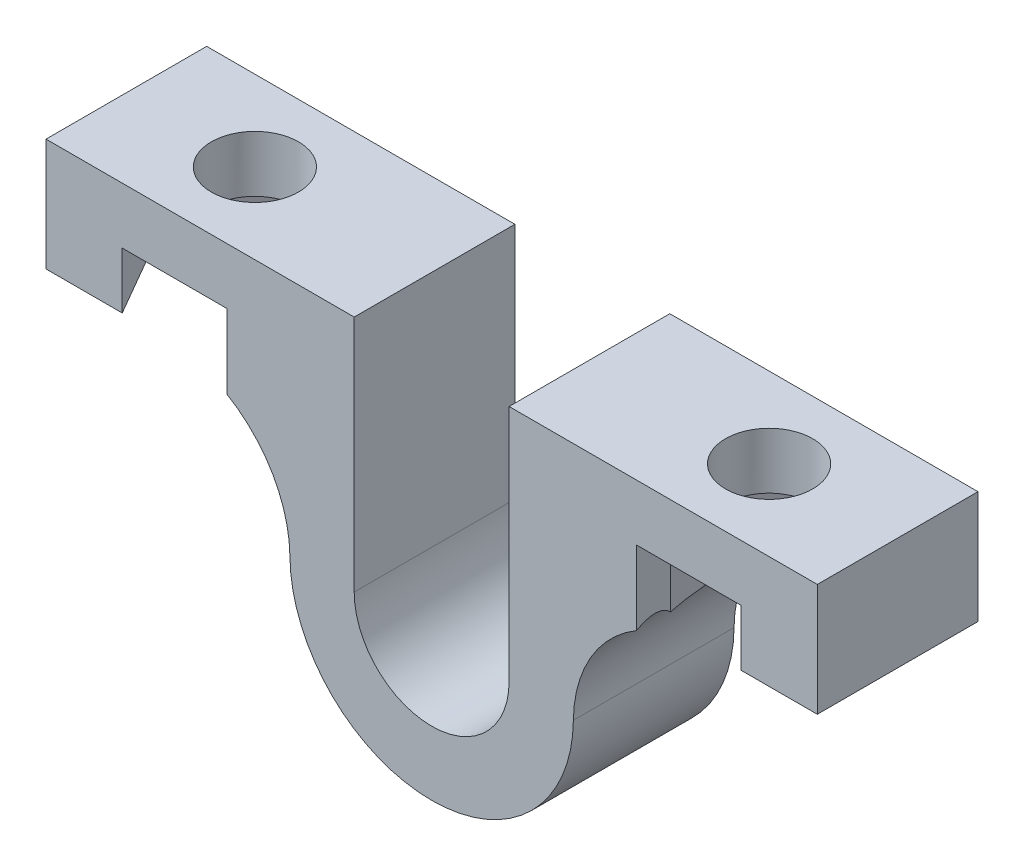
SolidWorks part; units mm, degrees
ref_plane "Front Plane" through (0, 0, 0) normal (0, 0, 1) x (1, 0, 0)
ref_plane "Top Plane" through (0, 0, 0) normal (0, 1, 0) x (1, 0, 0)
ref_plane "Right Plane" through (0, 0, 0) normal (1, 0, 0) x (0, 0, -1)
sketch "Sketch1" plane through (0, 0, 0) normal (0, 0, 1) x (1, 0, 0)
  line L2 (-19.05, 11.7634) -> (-19.05, 6.2071)
  line L6 (-3.8259, 0) -> (-3.8259, 11.7634)
  line L13 (-19.05, 6.2071) -> (-13.3501, 6.2071)
  line L15 (-19.05, 11.7634) -> (-3.8259, 11.7634)
  line L16 (0, -3.8259) -> (0, -7.0009)
  arc A0 (-3.8259, 0) -> (0, -3.8259) centre (0, 0) ccw
  arc A1 (-7.0005, -0.0749) -> (0, -7.0009) centre (0, 0) ccw
  arc A2 (-7.0005, -0.0749) -> (-13.3501, 6.2071) centre (-13.3501, -0.1429) ccw
  dimension "D1" = 7.6518
  dimension "D5" = 6.35
  dimension "D4" = 5.5562
  dimension "D6" = 19.05
  dimension "D2" = 3.175
  dimension "D3" = 15.5892
extrude "Boss-Extrude1" add sketch "Sketch1" along normal blind 7.9375
hole_wizard "#6 Clearance Hole1" positions "Sketch2" profile "Sketch3" hole size "#6" standard "ANSI Inch" end condition through all
sketch "Sketch2" plane through (0, 11.7634, 0) normal (0, 1, 0) x (1, 0, 0)
  line L0 (0, -1000) -> (0, 49000) construction
  line L1 (-1019.05, -3.9688) -> (48980.95, -3.9688) construction
  line L2 (-19.05, -7.9375) -> (-19.05, 0) construction
  point P0 (-12.7, -3.9688)
  point P15 (-19.05, -3.9688)
  point P17 (-12.7, -3.9688)
  dimension "D1" = 12.7
sketch "Sketch3" plane through (-12.7, 11.7634, 3.9688) normal (1, 0, 0) x (0, 0, 1)
  line L0 (0, 0) -> (0, 18.7643)
  line L1 (0, 18.7643) -> (2.1526, 18.7643)
  line L2 (2.1526, 18.7643) -> (2.1526, 0)
  line L5 (2.1526, 0) -> (0, 0)
  line L11 (0, -6.35) -> (0, 107.95) construction
  dimension "Thru Hole Dia." = 4.3053
  dimension "Thru Hole Depth" = 18.7643
sketch "Sketch4" plane through (0, 6.2071, 0) normal (0, -1, 0) x (1, 0, 0)
  line L1 (-17.576, 3.9688) -> (-15.138, -0.254)
  line L2 (-15.138, -0.254) -> (-10.262, -0.254)
  line L3 (-10.262, -0.254) -> (-7.824, 3.9688)
  line L4 (-7.824, 3.9688) -> (-10.262, 8.1915)
  line L5 (-10.262, 8.1915) -> (-15.138, 8.1915)
  line L6 (-15.138, 8.1915) -> (-17.576, 3.9688)
  circle A0 centre (-12.7, 3.9688) radius 4.2228 construction
  dimension "D1" = 8.4455
extrude "Cut-Extrude1" cut sketch "Sketch4" against normal blind 2.7781 and the other way through all
mirror "Mirror1" about plane through (0, -3.8259, 7.9375) normal (-1, 0, 0) of bodies 103 104
equation "\"D1@Sketch1\"=(0.25+(1/32))+0.02"
equation "\"D1@Sketch4\"=(5/16)+.02"
equation "\"D4@Sketch1\"=(7/32)"
equation "\"D1@Cut-Extrude1\"=(7/64)"
equation "\"D3@Sketch1\"=(0.25+(1/32)+.02)+(5/16)"
equation "\"D1@Boss-Extrude1\"=(5/16)"
